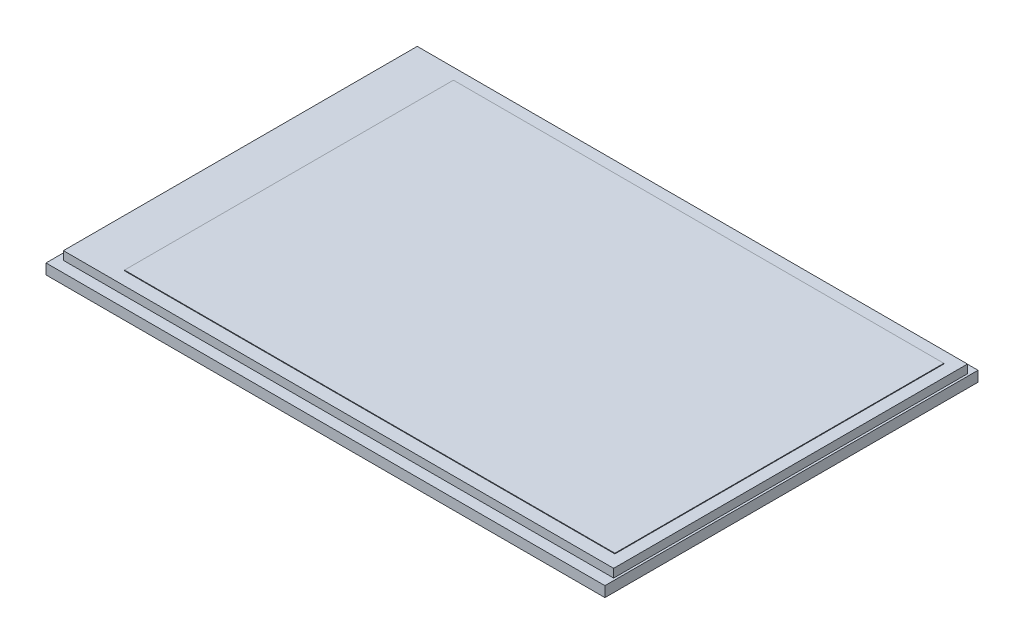
SolidWorks part; units mm, degrees
ref_plane "前视基准面" through (0, 0, 0) normal (0, 0, 1) x (1, 0, 0)
ref_plane "上视基准面" through (0, 0, 0) normal (0, 1, 0) x (1, 0, 0)
ref_plane "右视基准面" through (0, 0, 0) normal (1, 0, 0) x (0, 0, -1)
other "Configuration Table"
sketch "草图1" plane through (0, 0, 0) normal (0, 1, 0) x (1, 0, 0)
  line L1 (-44.7917, 23.8889) -> (41.2083, 23.8889)
  line L2 (-44.7917, 23.8889) -> (-44.7917, -33.5111)
  line L3 (-44.7917, -33.5111) -> (41.2083, -33.5111)
  line L4 (41.2083, 23.8889) -> (41.2083, -33.5111)
  dimension "D1" = 86
  dimension "D2" = 57.4
extrude "凸台-拉伸1" add sketch "草图1" along normal blind 1.6
sketch "草图2" plane through (0, 1.6, 0) normal (0, 1, 0) x (1, 0, 0)
  line L0 (41.2083, 23.8889) -> (-44.7917, 23.8889) construction
  line L1 (-43.7917, 22.6089) -> (40.8683, 22.6089)
  line L2 (-43.7917, 22.6089) -> (-43.7917, -31.8311)
  line L3 (-43.7917, -31.8311) -> (40.8683, -31.8311)
  line L4 (40.8683, 22.6089) -> (40.8683, -31.8311)
  line L5 (-44.7917, 23.8889) -> (-44.7917, -33.5111) construction
  point P8 (-51.2628, 12.2448)
  dimension "D1" = 84.66
  dimension "D2" = 54.44
  dimension "D3" = 1.28
  dimension "D4" = 1
extrude "凸台-拉伸2" add sketch "草图2" along normal blind 1.3
sketch "草图3" plane through (0, 2.9, 0) normal (0, 1, 0) x (1, 0, 0)
  line L1 (-36.4017, 20.7889) -> (39.0483, 20.7889)
  line L2 (-36.4017, 20.7889) -> (-36.4017, -29.8211)
  line L3 (-36.4017, -29.8211) -> (39.0483, -29.8211)
  line L4 (39.0483, 20.7889) -> (39.0483, -29.8211)
  line L5 (40.8683, 22.6089) -> (-43.7917, 22.6089) construction
  line L6 (40.8683, -31.8311) -> (40.8683, 22.6089) construction
  point P6 (40.8683, 22.6089)
  dimension "D1" = 75.45
  dimension "D2" = 50.61
  dimension "D3" = 1.82
  dimension "D4" = 1.82
extrude "凸台-拉伸3" add sketch "草图3" along normal blind 0.1
sketch "草图4" plane through (0, 0, 0) normal (0, -1, 0) x (1, 0, 0)
  line L0 (-44.7917, -23.8889) -> (-44.7917, 33.5111) construction
  line L1 (-37.2517, -17.1989) -> (13.9183, -17.1989)
  line L2 (-37.2517, -17.1989) -> (-37.2517, -22.1989)
  line L3 (-37.2517, -22.1989) -> (13.9183, -22.1989)
  line L4 (13.9183, -17.1989) -> (13.9183, -22.1989)
  line L5 (41.2083, -23.8889) -> (-44.7917, -23.8889) construction
  point P6 (-42.7519, -13.4969)
  dimension "D1" = 51.17
  dimension "D2" = 5
  dimension "D3" = 7.54
  dimension "D4" = 1.69
extrude "凸台-拉伸4" add sketch "草图4" along normal blind 14
